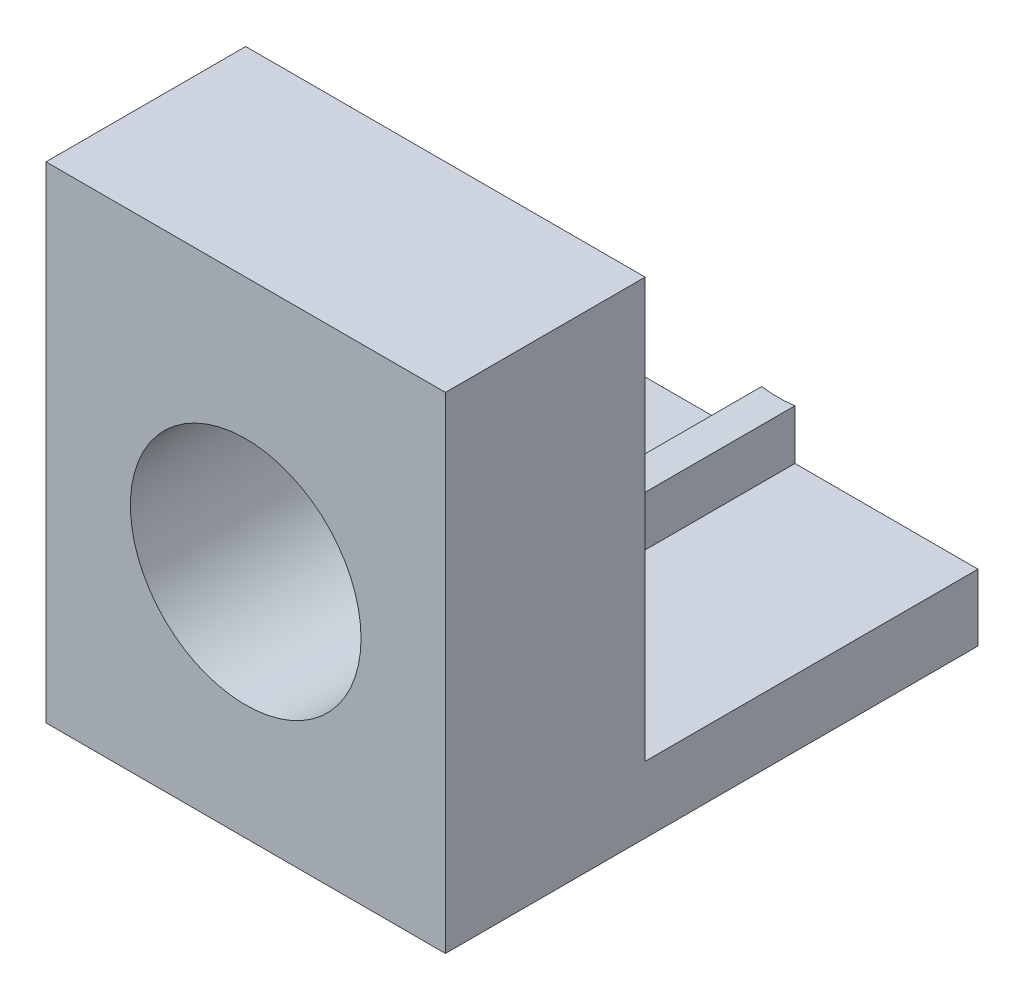
SolidWorks part; units mm, degrees
ref_plane "Front Plane" through (0, 0, 0) normal (0, 0, 1) x (1, 0, 0)
ref_plane "Top Plane" through (0, 0, 0) normal (0, 1, 0) x (1, 0, 0)
ref_plane "Right Plane" through (0, 0, 0) normal (1, 0, 0) x (0, 0, -1)
sketch "Sketch1" plane through (0, 0, 0) normal (0, 1, 0) x (1, 0, 0)
  line L1 (-19.05, 25.4) -> (19.05, 25.4)
  line L2 (-19.05, 25.4) -> (-19.05, -25.4)
  line L3 (-19.05, -25.4) -> (19.05, -25.4)
  line L4 (19.05, 25.4) -> (19.05, -25.4)
  line L5 (-19.05, 25.4) -> (19.05, -25.4) construction
  line L6 (-19.05, -25.4) -> (19.05, 25.4) construction
  point P0 (0, 0)
  dimension "D1" = 38.1
  dimension "D2" = 50.8
extrude "Boss-Extrude1" add sketch "Sketch1" along normal blind 6.35
sketch "Sketch2" plane through (0, 6.35, 0) normal (0, 1, 0) x (1, 0, 0)
  line L0 (19.05, 25.4) -> (-19.05, 25.4) construction
  line L1 (-1.5875, 25.4) -> (1.5875, 25.4)
  line L2 (-1.5875, 25.4) -> (-1.5875, -25.4)
  line L3 (-1.5875, -25.4) -> (1.5875, -25.4)
  line L4 (1.5875, 25.4) -> (1.5875, -25.4)
  line L5 (-19.05, -25.4) -> (19.05, -25.4) construction
  point P8 (0, -25.4)
  dimension "D1" = 3.175
extrude "Boss-Extrude2" add sketch "Sketch2" along normal blind 6.35
sketch "Sketch3" plane through (0, 6.35, 0) normal (0, 1, 0) x (1, 0, 0)
  line L0 (-19.05, 25.4) -> (-19.05, -25.4) construction
  line L1 (19.05, -25.4) -> (-19.05, -25.4)
  line L2 (19.05, -25.4) -> (19.05, -6.35)
  line L3 (19.05, -6.35) -> (-19.05, -6.35)
  line L4 (-19.05, -25.4) -> (-19.05, -6.35)
  dimension "D1" = 19.05
extrude "Boss-Extrude3" add sketch "Sketch3" along normal blind 40
sketch "Sketch4" plane through (0, 0, 25.4) normal (0, 0, 1) x (1, 0, 0)
  line L2 (-19.05, 0) -> (19.05, 0) construction
  circle A0 centre (0, 22) radius 11
  point P5 (0, 0)
  point P6 (-3.0222, 28.1884)
  point P7 (0, 0)
  dimension "D2" = 22
  dimension "D1" = 22
extrude "Cut-Extrude1" cut sketch "Sketch4" against normal through all
